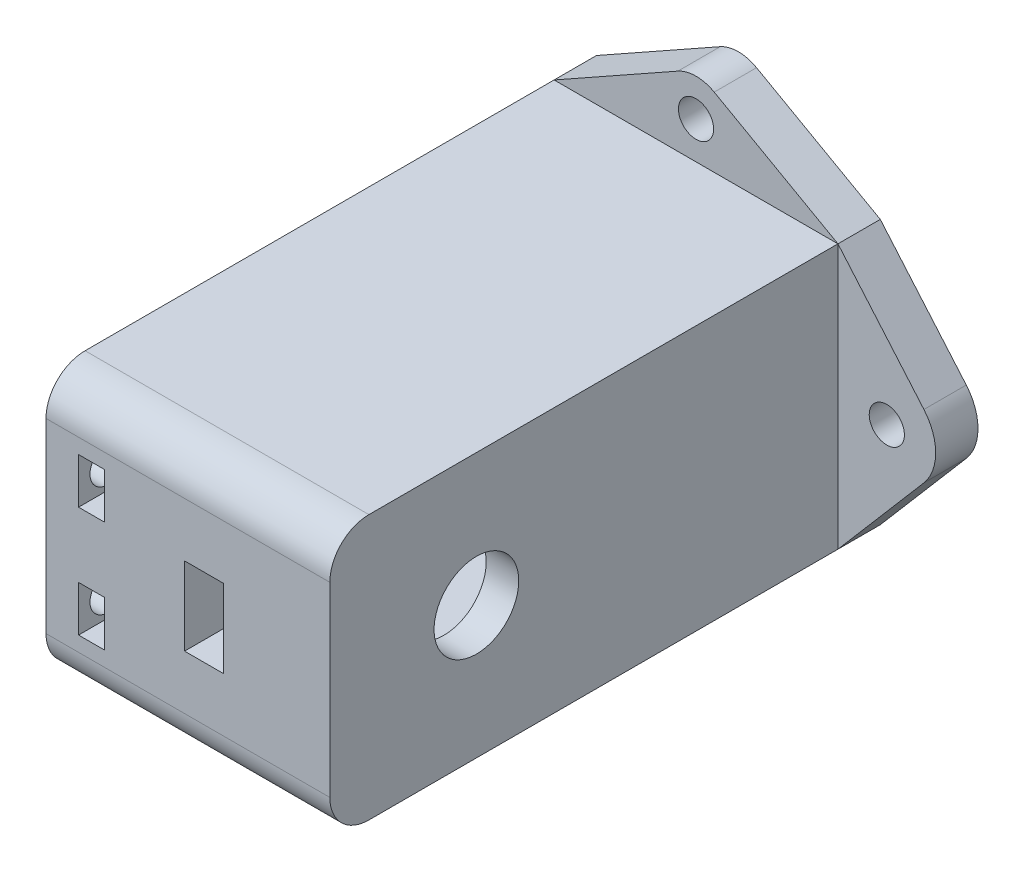
SolidWorks part; units mm, degrees
ref_plane "Front Plane" through (0, 0, 0) normal (0, 0, 1) x (1, 0, 0)
ref_plane "Top Plane" through (0, 0, 0) normal (0, 1, 0) x (1, 0, 0)
ref_plane "Right Plane" through (0, 0, 0) normal (1, 0, 0) x (0, 0, -1)
sketch "Sketch1" plane through (0, 0, 0) normal (0, 0, 1) x (1, 0, 0)
  line L0 (-19.5, 0) -> (-19.5, -15)
  line L1 (-19.5, 0) -> (-19.5, 15)
  line L2 (-19.5, 0) -> (-51.9, 0)
  line L3 (-19.5, 0) -> (12.9, 0)
  line L4 (12.9, 0) -> (12.9, -15)
  line L5 (29.0581, -15) -> (-10.5234, -15) construction
  line L6 (12.9, -15) -> (-51.9, -15)
  line L7 (-51.9, -15) -> (-51.9, 15)
  line L8 (-51.9, 15) -> (12.9, 15)
  line L9 (29.0581, 15) -> (-10.5234, 15) construction
  line L10 (12.9, 15) -> (12.9, 0)
extrude "Boss-Extrude1" add sketch "Sketch1" along normal blind 10 contours L10 L8 L1 L3 | L6 L4 L3 L0 | L7 L6 L0 L2 | L8 L7 L2 L1
sketch "Sketch4" plane through (0, 15, 0) normal (0, 1, 0) x (1, 0, 0)
  line L0 (-51.9, -10) -> (-25.3727, -10)
  line L1 (-51.9, -10) -> (12.9, -10) construction
  line L2 (-25.3727, -10) -> (-25.3727, 0)
  line L3 (-51.9, 0) -> (12.9, 0) construction
  line L4 (-25.3727, 0) -> (-51.9, 0)
  line L5 (-51.9, 0) -> (-51.9, -10)
extrude "Cut-Extrude2" cut sketch "Sketch4" against normal blind 80
sketch "Sketch5" plane through (-25.3727, 0, 0) normal (-1, 0, 0) x (0, 0, 1)
  circle A0 centre (5, -8.5) radius 2.75
  circle A1 centre (5, 8.5) radius 2.75
extrude "Cut-Extrude3" cut sketch "Sketch5" against normal blind 20
sketch "Sketch7" plane through (0, 0, 0) normal (0, 0, -1) x (-1, 0, 0)
  line L2 (-12.9, -15.3) -> (-13.2, -15.3)
  line L3 (-13.2, -15.3) -> (-13.2, 15.3)
  line L4 (-13.2, 15.3) -> (-12.9, 15.3)
  line L5 (-12.9, 15.3) -> (25.3727, 15.3)
  line L6 (25.3727, 15.3) -> (25.3727, 15)
  line L7 (-12.9, -15.3) -> (25.3727, -15.3)
  line L8 (25.3727, -15.3) -> (25.3727, -15)
  line L9 (25.3727, -15) -> (-12.9, -15)
  line L10 (-12.9, -15) -> (-12.9, 15)
  line L11 (-12.9, 15) -> (25.3727, 15)
extrude "Boss-Extrude2" add sketch "Sketch7" against normal up to surface (10 mm away) up to face at (-6.2363, 0, 10)
sketch "Sketch8" plane through (0, 0, 0) normal (0, 0, -1) x (-1, 0, 0)
  line L1 (25.3727, 15.3) -> (25.3727, 20.3)
  line L2 (25.3727, 20.3) -> (-13.2, 20.3)
  line L3 (-13.2, 20.3) -> (-18.2, 20.3)
  line L4 (-18.2, 20.3) -> (-18.2, -15.3)
  line L5 (-13.2, -20.3) -> (25.3727, -20.3)
  line L6 (-13.2, -20.3) -> (-18.2, -20.3)
  line L7 (-18.2, -20.3) -> (-18.2, -15.3)
  line L8 (25.3727, -20.3) -> (25.3727, -15.3)
  line L9 (25.3727, -15.3) -> (-13.2, -15.3)
  line L10 (-13.2, -15.3) -> (-13.2, 15.3)
  line L11 (-13.2, 15.3) -> (25.3727, 15.3)
extrude "Boss-Extrude3" add sketch "Sketch8" against normal offset from surface (75.5 mm away) 0.5
sketch "Sketch9" plane through (0, 0, 75.5) normal (0, 0, 1) x (1, 0, 0)
  line L1 (18.2, -20.3) -> (-25.3727, -20.3)
  line L2 (18.2, -20.3) -> (18.2, 20.3)
  line L3 (18.2, 20.3) -> (-25.3727, 20.3)
  line L4 (-25.3727, -20.3) -> (-25.3727, 20.3)
extrude "Boss-Extrude4" add sketch "Sketch9" along normal blind 9
fillet "Fillet1" radius 6 2 edges at (-3.5863, -20.3, 84.5) (-3.5863, 20.3, 84.5)
sketch "Sketch10" plane through (-25.3727, 0, 0) normal (-1, 0, 0) x (0, 0, 1)
  circle A0 centre (80, 8.5) radius 2.75
  circle A1 centre (80, -8.5) radius 2.75
extrude "Cut-Extrude4" cut sketch "Sketch10" against normal blind 20
sketch "Sketch11" plane through (0, 0, 84.5) normal (0, 0, 1) x (1, 0, 0)
  line L0 (-25.3727, 0) -> (-25.3727, -8.5)
  line L1 (-25.3727, 14.3) -> (-25.3727, -14.3) construction
  line L2 (-25.3727, 0) -> (-25.3727, 8.5)
  line L3 (-25.3727, 8.5) -> (-20.3727, 8.5)
  line L4 (-20.3727, 5) -> (-20.3727, 12)
  line L5 (-20.3727, 12) -> (-16.3727, 12)
  line L6 (-20.3727, 5) -> (-16.3727, 5)
  line L7 (-16.3727, 5) -> (-16.3727, 12)
  line L8 (-25.3727, 0) -> (-21.8707, 0)
  line L9 (-16.3727, -5) -> (-16.3727, -12)
  line L10 (-20.3727, -5) -> (-16.3727, -5)
  line L11 (-20.3727, -12) -> (-16.3727, -12)
  line L12 (-20.3727, -5) -> (-20.3727, -12)
  line L13 (-25.3727, -8.5) -> (-20.3727, -8.5)
extrude "Cut-Extrude5" cut sketch "Sketch11" against normal blind 122 contours L10 L12 L11 L9 | L6 L7 L5 L4
sketch "Sketch12" plane through (0, 0, 0) normal (0, 0, -1) x (-1, 0, 0)
  circle A0 centre (26.5, 0) radius 3
extrude "Boss-Extrude5" add sketch "Sketch12" against normal blind 1.2
sketch "Sketch13" plane through (0, 0, 0) normal (0, 0, 1) x (1, 0, 0)
  line L0 (18.2, 0) -> (10.566, 0)
  line L2 (18.2, -14.3) -> (18.2, 14.3) construction
  line L3 (18.2, 20.3) -> (-25.3727, 20.3)
  line L4 (-25.3727, -20.3) -> (-6.3779, -30.9696)
  line L5 (18.2, -20.3) -> (-0.7948, -30.9696)
  line L6 (18.2, -20.3) -> (-25.3727, -20.3)
  line L7 (18.2, 20.3) -> (-0.7948, 30.9696)
  line L8 (-25.3727, 20.3) -> (-6.3779, 30.9696)
  circle A0 centre (-3.5863, -26) radius 2.7
  arc A1 (-6.3779, -30.9696) -> (-0.7948, -30.9696) centre (-3.5863, -26) ccw
  arc A2 (-6.3779, 30.9696) -> (-0.7948, 30.9696) centre (-3.5863, 26) cw
  circle A3 centre (-3.5863, 26) radius 2.7
extrude "Boss-Extrude6" add sketch "Sketch13" along normal blind 6.5 contours A2 L8 L3 L7 A3 | L4 A1 L5 L6 A0
sketch "Sketch14" plane through (0, 0, 0) normal (0, 0, -1) x (-1, 0, 0)
  line L0 (25.3727, 20.3) -> (25.3727, 15.5)
  line L1 (25.3727, 2.7801) -> (25.3727, 20.3) construction
  line L2 (33.5, 15.5) -> (-33.5, 15.5) construction
  line L3 (25.3727, 17.9) -> (20.3727, 17.9)
  line L4 (20.3727, 17.9) -> (18.7492, 17.9)
  line L5 (25.3727, 20.3) -> (-18.2, 20.3)
  line L6 (3.5863, 20.3) -> (3.5863, 16.3092)
  line L7 (-18.2, 0) -> (-9.5157, 0)
  line L8 (-18.2, 20.3) -> (-18.2, -20.3) construction
  circle A0 centre (18.7492, 17.9) radius 1.5
  circle A1 centre (-11.5765, 17.9) radius 1.5
  circle A2 centre (-11.5765, -17.9) radius 1.5
  circle A3 centre (18.7492, -17.9) radius 1.5
extrude "Cut-Extrude6" cut sketch "Sketch14" against normal blind 8
sketch "Sketch15" plane through (13.2, 0, 0) normal (-1, 0, 0) x (0, 0, 1)
  circle A0 centre (62, 0) radius 4.2
extrude "Cut-Extrude7" cut sketch "Sketch15" against normal blind 8
sketch "Sketch16" plane through (0, 0, 0) normal (0, 0, -1) x (-1, 0, 0)
  line L0 (-23, 0) -> (-25.7, 0)
  line L2 (-18.2, -20.3) -> (-31.3984, -4.8763)
  line L3 (-18.2, 20.3) -> (-31.3984, 4.8763)
  line L4 (-18.2, 20.3) -> (-18.2, -20.3)
  circle A0 centre (-25.7, 0) radius 2.7
  arc A1 (-31.3984, 4.8763) -> (-31.3984, -4.8763) centre (-25.7, 0) ccw
  line M14 (-18.2, 20.3) -> (-18.2, -20.3)
extrude "Boss-Extrude9" add sketch "Sketch16" against normal up to surface (6.5 mm away) contours L3 A1 L2 A0 M14 up to face at (-0.8863, -26, 6.5)
sketch "Sketch17" plane through (0, 0, 0) normal (0, 0, -1) x (-1, 0, 0)
  line L0 (-18.2, 20.3) -> (-18.2, -20.3)
  line L2 (-18.2, 0) -> (-25.7, 0)
  circle A0 centre (-25.7, 0) radius 2.7
extrude "Cut-Extrude8" cut sketch "Sketch17" against normal blind 8
sketch "Sketch18" plane through (0, 0, 84.5) normal (0, 0, 1) x (1, 0, 0)
  line L0 (-26.1, 0) -> (-1.1, 0)
  line L1 (-26.1, 7.5) -> (-26.1, -7.5) construction
  line L3 (1.9, -6) -> (-4.1, -6)
  line L4 (1.9, -6) -> (1.9, 6)
  line L5 (1.9, 6) -> (-4.1, 6)
  line L6 (-4.1, -6) -> (-4.1, 6)
  line L7 (1.9, -6) -> (-4.1, 6) construction
  line L8 (1.9, 6) -> (-4.1, -6) construction
extrude "Cut-Extrude9" cut sketch "Sketch18" against normal blind 23
sketch "Sketch19" plane through (18.2, 0, 0) normal (1, 0, 0) x (0, 0, -1)
  circle A0 centre (-62, 0) radius 6.5
extrude "Cut-Extrude10" cut sketch "Sketch19" against normal blind 23
